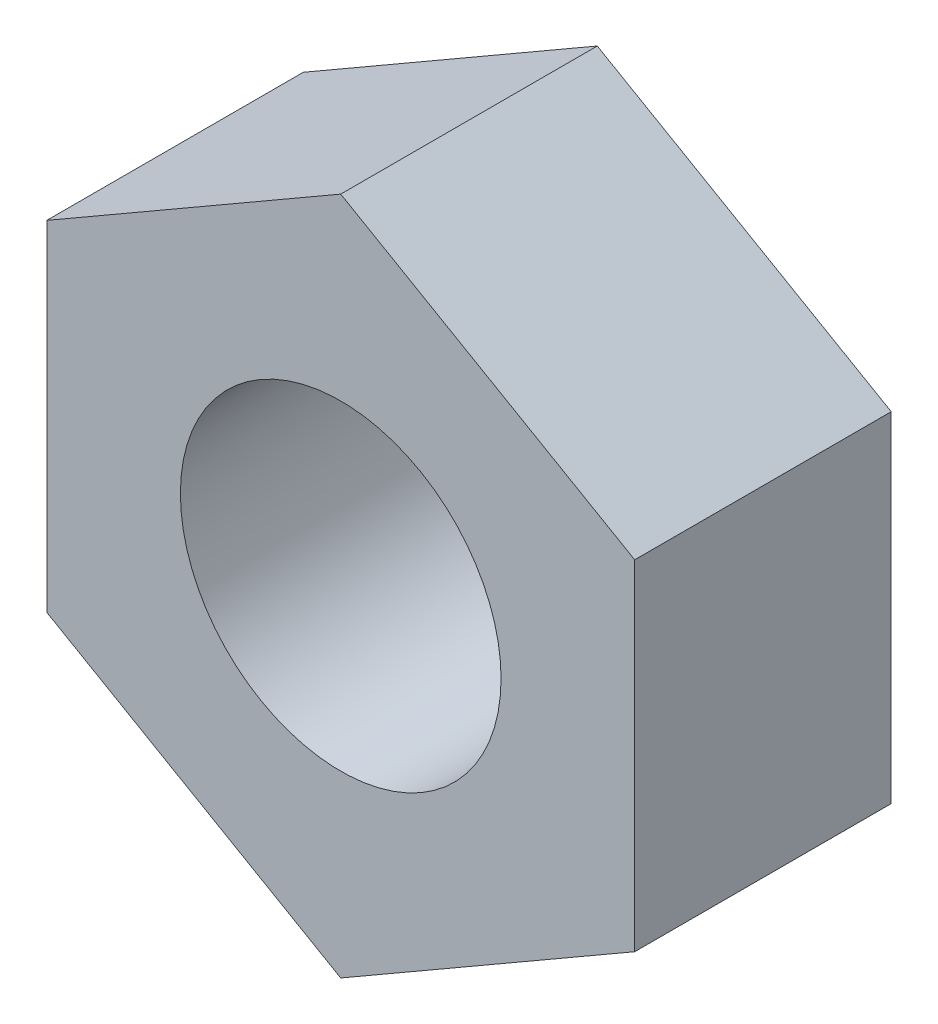
SolidWorks part; units mm, degrees
ref_plane "Front Plane" through (0, 0, 0) normal (0, 0, 1) x (1, 0, 0)
ref_plane "Top Plane" through (0, 0, 0) normal (0, 1, 0) x (1, 0, 0)
ref_plane "Right Plane" through (0, 0, 0) normal (1, 0, 0) x (0, 0, -1)
sketch "Sketch1" plane through (0, 0, 0) normal (0, 0, 1) x (1, 0, 0)
  line L0 (2.75, 1.5877) -> (0, 3.1754)
  line L1 (0, 3.1754) -> (-2.75, 1.5877)
  line L2 (-2.75, 1.5877) -> (-2.75, -1.5877)
  line L3 (-2.75, -1.5877) -> (0, -3.1754)
  line L4 (0, -3.1754) -> (2.75, -1.5877)
  line L5 (2.75, -1.5877) -> (2.75, 1.5877)
  circle A0 centre (0, 0) radius 1.5
extrude "Nut" add sketch "Sketch1" along normal blind 2.4 from offset 1.2
